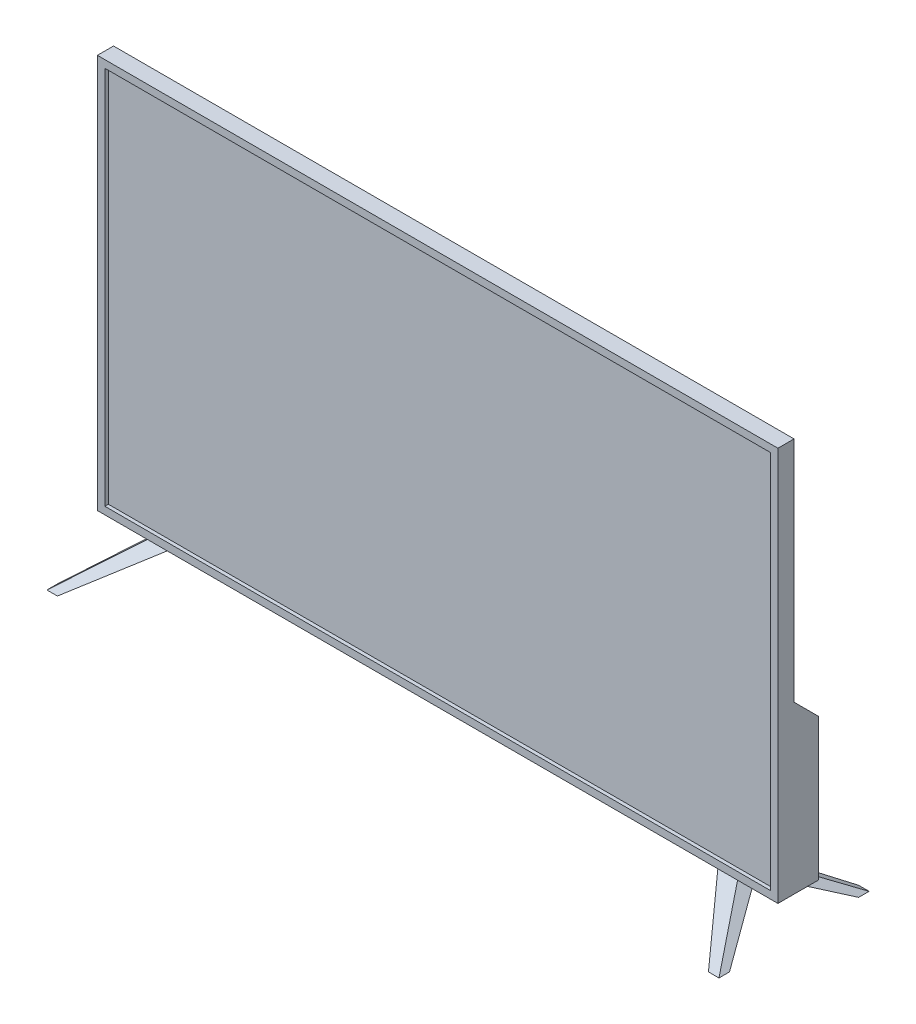
SolidWorks part; units mm, degrees
ref_plane "Front" through (0, 0, 0) normal (0, 0, 1) x (1, 0, 0)
ref_plane "Top" through (0, 0, 0) normal (0, 1, 0) x (1, 0, 0)
ref_plane "Right" through (0, 0, 0) normal (1, 0, 0) x (0, 0, -1)
sketch "Sketch2" plane through (0, 0, 0) normal (0, 0, 1) x (1, 0, 0)
  line L1 (615.95, 356.87) -> (-615.95, 356.87)
  line L2 (615.95, 356.87) -> (615.95, -356.87)
  line L3 (615.95, -356.87) -> (-615.95, -356.87)
  line L4 (-615.95, 356.87) -> (-615.95, -356.87)
  line L5 (0, -356.87) -> (0, 356.87) construction
  line L6 (615.95, 0) -> (-615.95, 0) construction
  point P0 (0, 0)
  dimension "D1" = 1231.9
  dimension "D2" = 713.74
extrude "Boss-Extrude1" add sketch "Sketch2" along normal blind 73.66
sketch "Sketch3" plane through (0, 0, 0) normal (1, 0, 0) x (0, 0, -1)
  line L0 (-49.53, -356.87) -> (-172.72, -427.99)
  line L1 (-73.66, -356.87) -> (0, -356.87) construction
  line L2 (-172.72, -427.99) -> (-153.67, -427.99)
  line L3 (-153.67, -427.99) -> (-36.83, -369.57)
  line L4 (-36.83, -369.57) -> (80.01, -427.99)
  line L5 (80.01, -427.99) -> (99.06, -427.99)
  line L6 (99.06, -427.99) -> (-24.13, -356.87)
  line L7 (-24.13, -356.87) -> (-49.53, -356.87)
  line L8 (-36.83, 356.87) -> (-36.83, -427.99) construction
  line L9 (-73.66, 356.87) -> (0, 356.87) construction
  point P13 (-150.9214, -427.99)
  dimension "D1" = 271.78
  dimension "D2" = 784.86
  dimension "D3" = 19.05
  dimension "D4" = 25.4
  dimension "D5" = 12.7
extrude "Boss-Extrude2" add sketch "Sketch3" along normal mid plane 1216.66
fillet "Fillet1" radius 12.7 1 edges at (0, -369.57, 36.83)
sketch "Sketch4" plane through (615.95, 0, 0) normal (1, 0, 0) x (0, 0, -1)
  line L1 (0, 356.87) -> (-44.45, 356.87)
  line L2 (0, 356.87) -> (0, -100.33)
  line L3 (0, -100.33) -> (-44.45, -55.88)
  line L4 (-44.45, 356.87) -> (-44.45, -55.88)
  point P5 (-44.45, 0)
  dimension "D1" = 44.45
  dimension "D2" = 457.2
  dimension "D3" = 45
extrude "Cut-Extrude1" cut sketch "Sketch4" against normal through all
sketch "Sketch5" plane through (0, 0, 0) normal (0, 0, 1) x (1, 0, 0)
  line L0 (-608.33, -427.99) -> (-523.5725, -356.87)
  line L1 (-615.95, -356.87) -> (615.95, -356.87) construction
  line L2 (-523.5725, -356.87) -> (-608.33, -356.87)
  line L3 (-608.33, -356.87) -> (-608.33, -427.99)
  line L4 (-589.28, -427.99) -> (-485.4725, -356.87)
  line L5 (608.33, -427.99) -> (-608.33, -427.99) construction
  line L6 (608.33, -356.87) -> (-608.33, -356.87) construction
  line L7 (-485.4725, -356.87) -> (485.4725, -356.87)
  line L8 (0, 0) -> (0, -356.87) construction
  line L9 (589.28, -427.99) -> (-589.28, -427.99)
  line L10 (589.28, -427.99) -> (485.4725, -356.87)
  line L11 (608.33, -356.87) -> (608.33, -427.99)
  line L12 (523.5725, -356.87) -> (608.33, -356.87)
  line L13 (608.33, -427.99) -> (523.5725, -356.87)
  point P19 (0, -427.99)
  dimension "D1" = 19.05
  dimension "D2" = 38.1
  dimension "D3" = 40
extrude "Cut-Extrude2" cut sketch "Sketch5" against normal mid plane 1216.66
sketch "Sketch6" plane through (0, 0, 73.66) normal (0, 0, 1) x (1, 0, 0)
  line L0 (-615.95, 0) -> (-602.4407, 0) construction
  line L1 (602.4407, 343.3607) -> (-602.4407, 343.3607)
  line L2 (602.4407, 343.3607) -> (602.4407, -343.3607)
  line L3 (602.4407, -343.3607) -> (-602.4407, -343.3607)
  line L4 (-602.4407, 343.3607) -> (-602.4407, -343.3607)
  line L5 (0, -343.3607) -> (0, 343.3607) construction
  line L6 (602.4407, 0) -> (-602.4407, 0) construction
  line L7 (-615.95, 356.87) -> (-615.95, -356.87) construction
  line L8 (0, 343.3607) -> (0, 356.87) construction
  line L9 (615.95, 356.87) -> (-615.95, 356.87) construction
  point P0 (0, 0)
  dimension "D1" = 1386.84
extrude "Cut-Extrude3" cut sketch "Sketch6" against normal blind 6.35
